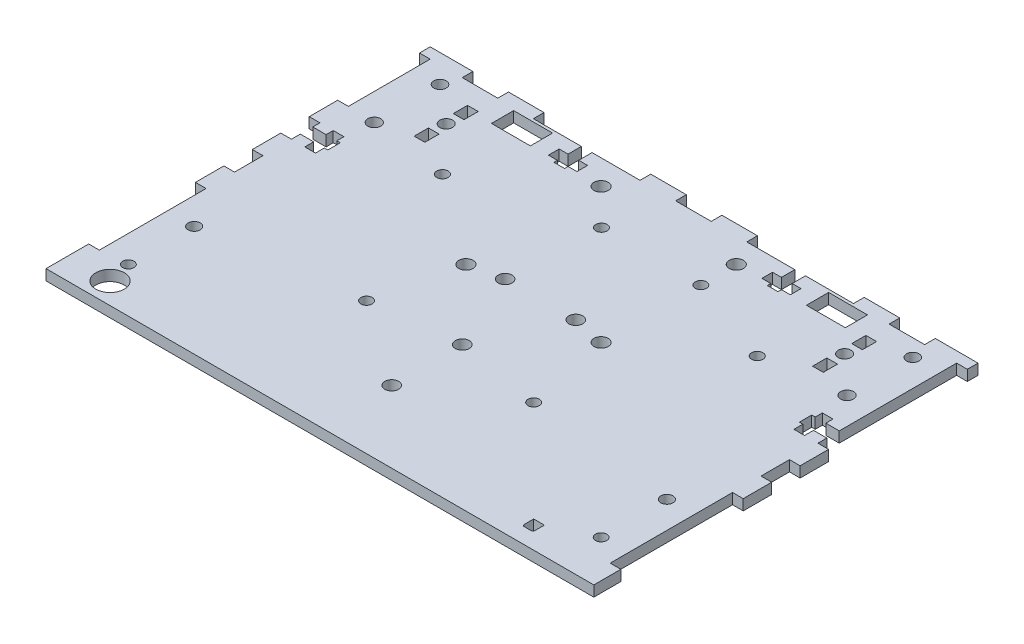
SolidWorks part; units mm, degrees
material "Balsa"
ref_plane "Alzado" through (0, 0, 0) normal (0, 0, 1) x (1, 0, 0)
ref_plane "Planta" through (0, 0, 0) normal (0, 1, 0) x (1, 0, 0)
ref_plane "Vista lateral" through (0, 0, 0) normal (1, 0, 0) x (0, 0, -1)
sketch "Croquis1" plane through (0, 0, 0) normal (0, 1, 0) x (1, 0, 0)
  line L0 (-77, 0) -> (-74, 0) construction
  line L1 (-77, -54) -> (77, -54)
  line L2 (-77, -54) -> (-77, 54)
  line L3 (-77, 54) -> (77, 54)
  line L4 (77, -54) -> (77, 54)
  line L5 (-77, -54) -> (77, 54) construction
  line L6 (-77, 54) -> (77, -54) construction
  line L7 (0, -54) -> (0, 54) construction
  line L8 (-74, 54) -> (-74, -54) construction
  line L9 (-77, -42) -> (-74, -42)
  line L10 (-77, 4) -> (-74, 4)
  line L11 (-77, 4) -> (-77, -4)
  line L12 (-77, -4) -> (-74, -4)
  line L13 (-74, 4) -> (-74, -4)
  line L14 (-77, 12) -> (-74, 12)
  line L15 (-77, 12) -> (-77, 20)
  line L16 (-77, 20) -> (-74, 20)
  line L17 (-74, 12) -> (-74, 20)
  line L22 (-77, 28) -> (-74, 28)
  line L23 (-77, 28) -> (-77, 42)
  line L24 (-77, 42) -> (-74, 42)
  line L25 (-74, 28) -> (-74, 42)
  line L26 (-74, -28) -> (-74, -42)
  line L27 (-77, -28) -> (-74, -28)
  line L28 (-77, -28) -> (-77, -42)
  line L29 (-77, -20) -> (-74, -20)
  line L30 (-74, -12) -> (-74, -20)
  line L31 (-77, -12) -> (-74, -12)
  line L32 (-77, -12) -> (-77, -20)
  line L33 (77, 42) -> (74, 42)
  line L34 (74, 28) -> (74, 42)
  line L35 (77, 28) -> (74, 28)
  line L36 (77, 28) -> (77, 42)
  line L37 (77, -28) -> (77, -42)
  line L38 (77, -28) -> (74, -28)
  line L39 (74, -28) -> (74, -42)
  line L40 (77, -42) -> (74, -42)
  line L41 (77, -12) -> (77, -20)
  line L42 (77, -12) -> (74, -12)
  line L43 (74, -12) -> (74, -20)
  line L44 (77, -20) -> (74, -20)
  line L45 (77, 20) -> (74, 20)
  line L46 (74, 12) -> (74, 20)
  line L47 (77, 12) -> (74, 12)
  line L48 (77, 12) -> (77, 20)
  line L49 (77, -4) -> (74, -4)
  line L50 (74, 4) -> (74, -4)
  line L51 (77, 4) -> (74, 4)
  line L52 (77, 4) -> (77, -4)
  line L53 (-77, 51) -> (77, 51) construction
  line L54 (-55, 51) -> (-65, 51)
  line L55 (-5, 54) -> (5, 54)
  line L56 (-5, 54) -> (-5, 51)
  line L57 (-5, 51) -> (5, 51)
  line L58 (5, 54) -> (5, 51)
  line L59 (15, 54) -> (45, 54)
  line L60 (15, 54) -> (15, 51)
  line L61 (15, 51) -> (45, 51)
  line L62 (45, 54) -> (45, 51)
  line L63 (55, 54) -> (65, 54)
  line L64 (55, 54) -> (55, 51)
  line L65 (55, 51) -> (65, 51)
  line L66 (65, 54) -> (65, 51)
  line L67 (-65, 54) -> (-65, 51)
  line L68 (-55, 54) -> (-65, 54)
  line L69 (-55, 54) -> (-55, 51)
  line L70 (-15, 51) -> (-45, 51)
  line L71 (-45, 54) -> (-45, 51)
  line L72 (-15, 54) -> (-45, 54)
  line L73 (-15, 54) -> (-15, 51)
  line L74 (-77, -48) -> (77, -48) construction
  line L75 (-30, 51) -> (-30, 10.4132) construction
  line L76 (53, -49.6) -> (55, -49.6)
  line L77 (52.5, -49.1) -> (52.5, -46.4)
  line L78 (52.5, -46.4) -> (55.5, -46.4)
  line L79 (55.5, -49.1) -> (55.5, -46.4)
  line L80 (52.5, -49.6) -> (55.5, -46.4) construction
  line L81 (52.5, -46.4) -> (55.5, -49.6) construction
  line L83 (-74, 1.5) -> (-74, -1.5)
  line L90 (-31.5, 51) -> (-28.5, 51)
  line L91 (-31.5, 51) -> (-31.5, 43.27)
  line L92 (-31.5, 43.27) -> (-28.5, 43.27)
  line L93 (-28.5, 51) -> (-28.5, 43.27)
  line L94 (-34, 47.25) -> (-26, 47.25)
  line L95 (-34, 47.25) -> (-34, 44.25)
  line L96 (-34, 44.25) -> (-26, 44.25)
  line L97 (-26, 47.25) -> (-26, 44.25)
  line L98 (31.5, 43.27) -> (28.5, 43.27)
  line L99 (28.5, 51) -> (28.5, 43.27)
  line L100 (31.5, 51) -> (28.5, 51)
  line L101 (31.5, 51) -> (31.5, 43.27)
  line L102 (34, 44.25) -> (26, 44.25)
  line L103 (26, 47.25) -> (26, 44.25)
  line L104 (34, 47.25) -> (26, 47.25)
  line L105 (34, 47.25) -> (34, 44.25)
  line L109 (74, 1.5) -> (74, -1.5)
  line L114 (-74, 16) -> (74, 16) construction
  line L115 (74, 17.9921) -> (66.27, 17.9921)
  line L116 (-74, 14.4979) -> (-66.27, 14.4979)
  line L117 (-74, 14.4979) -> (-74, 17.9921)
  line L118 (-74, 17.9921) -> (-66.27, 17.9921)
  line L119 (-66.27, 14.4979) -> (-66.27, 17.9921)
  line L120 (-70.25, 12) -> (-67.25, 12)
  line L121 (-70.25, 12) -> (-70.25, 20)
  line L122 (-70.25, 20) -> (-67.25, 20)
  line L123 (-67.25, 12) -> (-67.25, 20)
  line L124 (66.27, 14.4979) -> (66.27, 17.9921)
  line L125 (74, 0) -> (77, 0) construction
  line L126 (74, 14.4979) -> (66.27, 14.4979)
  line L127 (74, 14.4979) -> (74, 17.9921)
  line L128 (70.25, 20) -> (67.25, 20)
  line L129 (67.25, 12) -> (67.25, 20)
  line L130 (70.25, 12) -> (67.25, 12)
  line L131 (70.25, 12) -> (70.25, 20)
  circle A0 centre (-65, -48) radius 4
  arc A1 (55.5, -49.1) -> (55, -49.6) centre (55, -49.1) cw
  arc A2 (53, -49.6) -> (52.5, -49.1) centre (53, -49.1) cw
  point P0 (0, 0)
  point P78 (54, -48)
  point P123 (-75.5, 4)
  dimension "D17" = 8
  dimension "D22" = 0.5
  dimension "D1" = 108
  dimension "D2" = 154
  dimension "D3" = 3
  dimension "D4" = 4
  dimension "D5" = 3
  dimension "D6" = 8
  dimension "D7" = 8
  dimension "D8" = 8
  dimension "D9" = 14
  dimension "D10" = 3
  dimension "D11" = 5
  dimension "D12" = 10
  dimension "D13" = 10
  dimension "D14" = 30
  dimension "D15" = 10
  dimension "D16" = 10
  dimension "D18" = 6
  dimension "D19" = 23
  dimension "D20" = 3.2
  dimension "D21" = 3
  dimension "D23" = 12
  dimension "D31" = 3
  dimension "D32" = 8
  dimension "D33" = 1.5
  dimension "D34" = 4
  dimension "D35" = 0.98
  dimension "D36" = 7.73
  dimension "D37" = 8
  dimension "D38" = 7.73
  dimension "D39" = 3.4942
  dimension "D40" = 1.5021
  dimension "D41" = 0.98
  dimension "D42" = 8
  dimension "D43" = 4
  dimension "D44" = 3
extrude "Saliente-Extruir1" add sketch "Croquis1" along normal mid plane 2.9945
sketch "Croquis12" plane through (0, -1.4973, 0) normal (0, -1, 0) x (1, 0, 0)
  line L0 (77, 54) -> (77, 42) construction
  line L1 (-74, -51) -> (-77, -51)
  line L2 (-74, -51) -> (-74, -28)
  line L3 (-74, -28) -> (-77, -28)
  line L4 (-77, -51) -> (-77, -28)
  line L5 (-74, 20) -> (-77, 20)
  line L6 (-74, 20) -> (-74, 28)
  line L7 (-74, 28) -> (-77, 28)
  line L8 (-77, 20) -> (-77, 28)
  line L9 (74, -20) -> (77, -20)
  line L10 (74, -20) -> (74, -28)
  line L11 (74, -28) -> (77, -28)
  line L12 (77, -20) -> (77, -28)
  line L13 (74, 28) -> (77, 28)
  line L14 (74, 28) -> (74, 46.4)
  line L15 (74, 46.4) -> (77, 46.4)
  line L16 (77, 28) -> (77, 46.4)
  line L17 (77, -42) -> (77, -54) construction
  line L18 (74, -42) -> (77, -42)
  line L19 (74, -42) -> (74, -51)
  line L20 (74, -51) -> (77, -51)
  line L21 (77, -42) -> (77, -51)
extrude "Cortar-Extruir10" cut sketch "Croquis12" against normal blind 10
sketch "Croquis13" plane through (0, -1.4973, 0) normal (0, -1, 0) x (1, 0, 0)
  line L1 (77, 20) -> (74, 20)
  line L2 (77, 20) -> (77, 28)
  line L3 (77, 28) -> (74, 28)
  line L4 (74, 20) -> (74, 28)
extrude "Cortar-Extruir11" cut sketch "Croquis13" against normal blind 10
sketch "Croquis15" plane through (0, 1.4973, 0) normal (0, 1, 0) x (1, 0, 0)
  circle A0 centre (-8.89, 34.0361) radius 1.5875
  circle A1 centre (19.05, 34.0361) radius 1.5875
  circle A2 centre (24.13, -18.0339) radius 1.5875
  circle A3 centre (-24.13, -16.7639) radius 1.5875
extrude "Cortar-Extruir13" cut sketch "Croquis15" against normal blind 10
sketch "Croquis17" plane through (0, 1.4973, 0) normal (0, 1, 0) x (1, 0, 0)
  line L0 (72.1688, -24.6615) -> (72.1688, 30.6593) construction
  line L1 (72.1688, 2.9989) -> (49.0679, 2.9989) construction
  circle A0 centre (66.448, -41.3962) radius 1.5723
  circle A1 centre (66.448, -22.8957) radius 1.7053
sketch "Croquis16" plane through (0, 1.4973, 0) normal (0, 1, 0) x (1, 0, 0)
  circle A0 centre (-6.8282, -1.45) radius 2.1
  circle A1 centre (-44.8282, -1.45) radius 2.1
  circle A2 centre (-6.8282, -39.45) radius 2.1
  circle A3 centre (-44.8282, -39.45) radius 2
  circle A4 centre (30.775, -4.4) radius 1.9519
  circle A5 centre (10.925, -4.4) radius 1.95
  dimension "D1" = 3.9
extrude "Cortar-Extruir14" [suppressed] cut sketch "Croquis16" against normal blind 10
sketch "Croquis18" plane through (0, 1.4973, 0) normal (0, 1, 0) x (1, 0, 0)
  line L0 (0, 0) -> (0, 34.2841) construction
  circle A0 centre (66.448, -22.8957) radius 1.7053
  circle A1 centre (66.448, -41.3962) radius 1.5723
  circle A2 centre (66.448, 46.2165) radius 1.7517
  circle A3 centre (66.448, 27.7417) radius 1.8229
  circle A4 centre (-66.448, 27.7417) radius 1.8229
  circle A5 centre (-66.448, 46.2165) radius 1.7517
  circle A6 centre (-66.448, -41.3962) radius 1.5723
  circle A7 centre (-66.448, -22.8957) radius 1.7053
extrude "Cortar-Extruir15" cut sketch "Croquis18" against normal blind 10
sketch "Croquis19" plane through (0, 1.4973, 0) normal (0, 1, 0) x (1, 0, 0)
  line L0 (-56, 34) -> (-56, 41) construction
  line L1 (-57.5, 30) -> (-54.5, 30)
  line L2 (-57.5, 30) -> (-57.5, 34)
  line L3 (-57.5, 34) -> (-54.5, 34)
  line L4 (-54.5, 30) -> (-54.5, 34)
  line L5 (-56, 37.5) -> (-50.4082, 37.5) construction
  line L6 (-57.5, 41) -> (-54.5, 41)
  line L7 (-57.5, 45) -> (-57.5, 41)
  line L8 (-57.5, 45) -> (-54.5, 45)
  line L9 (-54.5, 45) -> (-54.5, 41)
  line L10 (0, 0) -> (0, 27.6562) construction
  line L11 (56, 37.5) -> (50.4082, 37.5) construction
  line L12 (56, 34) -> (56, 41) construction
  line L13 (54.5, 45) -> (54.5, 41)
  line L14 (57.5, 45) -> (54.5, 45)
  line L15 (57.5, 45) -> (57.5, 41)
  line L16 (57.5, 41) -> (54.5, 41)
  line L17 (54.5, 30) -> (54.5, 34)
  line L18 (57.5, 34) -> (54.5, 34)
  line L19 (57.5, 30) -> (57.5, 34)
  line L20 (57.5, 30) -> (54.5, 30)
  circle A0 centre (-56, 37.5) radius 1.8
  circle A1 centre (56, 37.5) radius 1.8
  dimension "D1" = 3.6
extrude "Cortar-Extruir16" cut sketch "Croquis19" against normal blind 10
sketch "Croquis20" plane through (0, 1.4973, 0) normal (0, 1, 0) x (1, 0, 0)
  line L1 (-38.7976, 43.9593) -> (-49.7367, 43.9593)
  line L2 (-38.7976, 43.9593) -> (-38.7976, 50.2033)
  line L3 (-38.7976, 50.2033) -> (-49.7367, 50.2033)
  line L4 (-49.7367, 43.9593) -> (-49.7367, 50.2033)
  circle A0 centre (-44.25, 24.7) radius 1.6
extrude "Cortar-Extruir17" cut sketch "Croquis20" against normal blind 10
mirror "Simetría1" about plane through (0, 0, 0) normal (1, 0, 0) of "Cortar-Extruir17"
sketch "Croquis21" plane through (0, 1.4973, 0) normal (0, 1, 0) x (1, 0, 0)
  circle A0 centre (0, -33.825) radius 1.9519
  circle A1 centre (0, -13.975) radius 1.9519
  circle A2 centre (19, 6.05) radius 2
  circle A3 centre (19, 44.05) radius 2
  circle A4 centre (-19, 44.05) radius 2
  circle A5 centre (-19, 6.05) radius 2
extrude "Cortar-Extruir18" cut sketch "Croquis21" against normal blind 10
sketch "Croquis22" plane through (0, 1.4973, 0) normal (0, 1, 0) x (1, 0, 0)
  circle A0 centre (-9.925, 8) radius 1.9519
  circle A1 centre (9.925, 8) radius 1.9519
extrude "Cortar-Extruir19" cut sketch "Croquis22" against normal blind 10
sketch "Croquis23" plane through (0, 1.4973, 0) normal (0, 1, 0) x (1, 0, 0)
  line L0 (-68.3649, 27.6945) -> (-64.3832, 27.6945)
  line L1 (-68.4388, 46.0665) -> (-64.4571, 46.0665)
  line L2 (-68.4388, 46.0665) -> (-68.4388, 46.3665)
  line L3 (-68.4388, 46.3665) -> (-64.4571, 46.3665)
  line L4 (-64.4571, 46.0665) -> (-64.4571, 46.3665)
  line L5 (-68.4388, 46.0665) -> (-64.4571, 46.3665) construction
  line L6 (-68.4388, 46.3665) -> (-64.4571, 46.0665) construction
  line L7 (-66.598, 44.2173) -> (-66.298, 44.2173)
  line L8 (-66.598, 44.2173) -> (-66.598, 48.2158)
  line L9 (-66.598, 48.2158) -> (-66.298, 48.2158)
  line L10 (-66.298, 44.2173) -> (-66.298, 48.2158)
  line L11 (-66.598, 44.2173) -> (-66.298, 48.2158) construction
  line L12 (-66.598, 48.2158) -> (-66.298, 44.2173) construction
  line L13 (-68.3649, 27.6945) -> (-68.3649, 27.9945)
  line L14 (-68.3649, 27.9945) -> (-64.3832, 27.9945)
  line L15 (-64.3832, 27.6945) -> (-64.3832, 27.9945)
  line L16 (-68.3649, 27.6945) -> (-64.3832, 27.9945) construction
  line L17 (-68.3649, 27.9945) -> (-64.3832, 27.6945) construction
  line L18 (-66.524, 25.8453) -> (-66.224, 25.8453)
  line L19 (-66.524, 25.8453) -> (-66.524, 29.8438)
  line L20 (-66.524, 29.8438) -> (-66.224, 29.8438)
  line L21 (-66.224, 25.8453) -> (-66.224, 29.8438)
  line L22 (-66.524, 25.8453) -> (-66.224, 29.8438) construction
  line L23 (-66.524, 29.8438) -> (-66.224, 25.8453) construction
  line L28 (-68.4428, -41.592) -> (-64.4611, -41.592)
  line L29 (-68.4428, -41.592) -> (-68.4428, -41.292)
  line L34 (-68.4428, -41.292) -> (-64.4611, -41.292)
  line L35 (-64.4611, -41.592) -> (-64.4611, -41.292)
  line L40 (-68.4428, -41.592) -> (-64.4611, -41.292) construction
  line L41 (-68.4428, -41.292) -> (-64.4611, -41.592) construction
  line L46 (-66.6019, -43.4413) -> (-66.3019, -43.4413)
  line L47 (-66.6019, -43.4413) -> (-66.6019, -39.4428)
  line L48 (-66.6019, -39.4428) -> (-66.3019, -39.4428)
  line L49 (-66.3019, -43.4413) -> (-66.3019, -39.4428)
  line L50 (-66.6019, -43.4413) -> (-66.3019, -39.4428) construction
  line L51 (-66.6019, -39.4428) -> (-66.3019, -43.4413) construction
  line L52 (-68.5357, -22.9687) -> (-64.5539, -22.9687)
  line L53 (-68.5357, -22.9687) -> (-68.5357, -22.6687)
  line L54 (-68.5357, -22.6687) -> (-64.5539, -22.6687)
  line L55 (-64.5539, -22.9687) -> (-64.5539, -22.6687)
  line L56 (-68.5357, -22.9687) -> (-64.5539, -22.6687) construction
  line L57 (-68.5357, -22.6687) -> (-64.5539, -22.9687) construction
  line L58 (-66.6948, -24.8179) -> (-66.3948, -24.8179)
  line L59 (-66.6948, -24.8179) -> (-66.6948, -20.8194)
  line L60 (-66.6948, -20.8194) -> (-66.3948, -20.8194)
  line L61 (-66.3948, -24.8179) -> (-66.3948, -20.8194)
  line L62 (-66.6948, -24.8179) -> (-66.3948, -20.8194) construction
  line L63 (-66.6948, -20.8194) -> (-66.3948, -24.8179) construction
  line L64 (64.4797, -41.6408) -> (68.4615, -41.6408)
  line L65 (64.4797, -41.6408) -> (64.4797, -41.3408)
  line L66 (64.4797, -41.3408) -> (68.4615, -41.3408)
  line L67 (68.4615, -41.6408) -> (68.4615, -41.3408)
  line L68 (64.4797, -41.6408) -> (68.4615, -41.3408) construction
  line L69 (64.4797, -41.3408) -> (68.4615, -41.6408) construction
  line L70 (66.3206, -43.4901) -> (66.6206, -43.4901)
  line L71 (66.3206, -43.4901) -> (66.3206, -39.4915)
  line L72 (66.3206, -39.4915) -> (66.6206, -39.4915)
  line L73 (66.6206, -43.4901) -> (66.6206, -39.4915)
  line L74 (66.3206, -43.4901) -> (66.6206, -39.4915) construction
  line L75 (66.3206, -39.4915) -> (66.6206, -43.4901) construction
  line L76 (64.4625, -22.7879) -> (68.4443, -22.7879)
  line L77 (64.4625, -22.7879) -> (64.4625, -22.4879)
  line L78 (64.4625, -22.4879) -> (68.4443, -22.4879)
  line L79 (68.4443, -22.7879) -> (68.4443, -22.4879)
  line L80 (64.4625, -22.7879) -> (68.4443, -22.4879) construction
  line L81 (64.4625, -22.4879) -> (68.4443, -22.7879) construction
  line L82 (66.3034, -24.6372) -> (66.6034, -24.6372)
  line L83 (66.3034, -24.6372) -> (66.3034, -20.6387)
  line L84 (66.3034, -20.6387) -> (66.6034, -20.6387)
  line L85 (66.6034, -24.6372) -> (66.6034, -20.6387)
  line L86 (66.3034, -24.6372) -> (66.6034, -20.6387) construction
  line L87 (66.3034, -20.6387) -> (66.6034, -24.6372) construction
  line L88 (64.4162, 27.4546) -> (68.3979, 27.4546)
  line L89 (64.4162, 27.4546) -> (64.4162, 27.7546)
  line L90 (64.4162, 27.7546) -> (68.3979, 27.7546)
  line L91 (68.3979, 27.4546) -> (68.3979, 27.7546)
  line L92 (64.4162, 27.4546) -> (68.3979, 27.7546) construction
  line L93 (64.4162, 27.7546) -> (68.3979, 27.4546) construction
  line L94 (66.2571, 25.6054) -> (66.5571, 25.6054)
  line L95 (66.2571, 25.6054) -> (66.2571, 29.6039)
  line L96 (66.2571, 29.6039) -> (66.5571, 29.6039)
  line L97 (66.5571, 25.6054) -> (66.5571, 29.6039)
  line L98 (66.2571, 25.6054) -> (66.5571, 29.6039) construction
  line L99 (66.2571, 29.6039) -> (66.5571, 25.6054) construction
  line L100 (64.3241, 46.1595) -> (68.3059, 46.1595)
  line L101 (64.3241, 46.1595) -> (64.3241, 46.4595)
  line L102 (64.3241, 46.4595) -> (68.3059, 46.4595)
  line L103 (68.3059, 46.1595) -> (68.3059, 46.4595)
  line L104 (64.3241, 46.1595) -> (68.3059, 46.4595) construction
  line L105 (64.3241, 46.4595) -> (68.3059, 46.1595) construction
  line L106 (66.165, 44.3102) -> (66.465, 44.3102)
  line L107 (66.165, 44.3102) -> (66.165, 48.3088)
  line L108 (66.165, 48.3088) -> (66.465, 48.3088)
  line L109 (66.465, 44.3102) -> (66.465, 48.3088)
  line L110 (66.165, 44.3102) -> (66.465, 48.3088) construction
  line L111 (66.165, 48.3088) -> (66.465, 44.3102) construction
  line L112 (-1.9679, -33.9155) -> (2.0138, -33.9155)
  line L113 (-1.9679, -33.9155) -> (-1.9679, -33.6155)
  line L114 (-1.9679, -33.6155) -> (2.0138, -33.6155)
  line L115 (2.0138, -33.9155) -> (2.0138, -33.6155)
  line L116 (-1.9679, -33.9155) -> (2.0138, -33.6155) construction
  line L117 (-1.9679, -33.6155) -> (2.0138, -33.9155) construction
  line L118 (-0.127, -35.7648) -> (0.173, -35.7648)
  line L119 (-0.127, -35.7648) -> (-0.127, -31.7663)
  line L120 (-0.127, -31.7663) -> (0.173, -31.7663)
  line L121 (0.173, -35.7648) -> (0.173, -31.7663)
  line L122 (-0.127, -35.7648) -> (0.173, -31.7663) construction
  line L123 (-0.127, -31.7663) -> (0.173, -35.7648) construction
  line L128 (-21.6618, 43.8673) -> (-16.5489, 43.8673)
  line L129 (-21.6618, 43.8673) -> (-21.6618, 44.1673)
  line L134 (-21.6618, 44.1673) -> (-16.5489, 44.1673)
  line L135 (-16.5489, 43.8673) -> (-16.5489, 44.1673)
  line L136 (-26.0528, -16.9261) -> (-22.0711, -16.9261)
  line L137 (-26.0528, -16.9261) -> (-26.0528, -16.6261)
  line L138 (-26.0528, -16.6261) -> (-22.0711, -16.6261)
  line L139 (-22.0711, -16.9261) -> (-22.0711, -16.6261)
  line L140 (-26.0528, -16.9261) -> (-22.0711, -16.6261) construction
  line L141 (-26.0528, -16.6261) -> (-22.0711, -16.9261) construction
  line L142 (-24.212, -18.7754) -> (-23.912, -18.7754)
  line L143 (-24.212, -18.7754) -> (-24.212, -14.7769)
  line L144 (-24.212, -14.7769) -> (-23.912, -14.7769)
  line L145 (-23.912, -18.7754) -> (-23.912, -14.7769)
  line L146 (-24.212, -18.7754) -> (-23.912, -14.7769) construction
  line L147 (-24.212, -14.7769) -> (-23.912, -18.7754) construction
  line L148 (22.1176, -18.1484) -> (26.0994, -18.1484)
  line L149 (22.1176, -18.1484) -> (22.1176, -17.8484)
  line L150 (22.1176, -17.8484) -> (26.0994, -17.8484)
  line L151 (26.0994, -18.1484) -> (26.0994, -17.8484)
  line L152 (22.1176, -18.1484) -> (26.0994, -17.8484) construction
  line L153 (22.1176, -17.8484) -> (26.0994, -18.1484) construction
  line L154 (23.9585, -19.9977) -> (24.2585, -19.9977)
  line L155 (23.9585, -19.9977) -> (23.9585, -15.9992)
  line L156 (23.9585, -15.9992) -> (24.2585, -15.9992)
  line L157 (24.2585, -19.9977) -> (24.2585, -15.9992)
  line L158 (23.9585, -19.9977) -> (24.2585, -15.9992) construction
  line L159 (23.9585, -15.9992) -> (24.2585, -19.9977) construction
  line L164 (-21.6618, 43.8673) -> (-16.5489, 44.1673) construction
  line L165 (-21.6618, 44.1673) -> (-16.5489, 43.8673) construction
  line L170 (-19.2554, 41.2583) -> (-18.9554, 41.2583)
  line L171 (-19.2554, 41.2583) -> (-19.2554, 46.7764)
  line L172 (16.9745, 33.9938) -> (20.9562, 33.9938)
  line L173 (16.9745, 33.9938) -> (16.9745, 34.2938)
  line L174 (16.9745, 34.2938) -> (20.9562, 34.2938)
  line L175 (20.9562, 33.9938) -> (20.9562, 34.2938)
  line L176 (16.9745, 33.9938) -> (20.9562, 34.2938) construction
  line L177 (16.9745, 34.2938) -> (20.9562, 33.9938) construction
  line L178 (18.8154, 32.1445) -> (19.1154, 32.1445)
  line L179 (18.8154, 32.1445) -> (18.8154, 36.143)
  line L180 (18.8154, 36.143) -> (19.1154, 36.143)
  line L181 (19.1154, 32.1445) -> (19.1154, 36.143)
  line L182 (18.8154, 32.1445) -> (19.1154, 36.143) construction
  line L183 (18.8154, 36.143) -> (19.1154, 32.1445) construction
  line L184 (-10.8981, 33.9741) -> (-6.9164, 33.9741)
  line L185 (-10.8981, 33.9741) -> (-10.8981, 34.2741)
  line L186 (-10.8981, 34.2741) -> (-6.9164, 34.2741)
  line L187 (-6.9164, 33.9741) -> (-6.9164, 34.2741)
  line L188 (-10.8981, 33.9741) -> (-6.9164, 34.2741) construction
  line L189 (-10.8981, 34.2741) -> (-6.9164, 33.9741) construction
  line L190 (-9.0572, 32.1249) -> (-8.7572, 32.1249)
  line L191 (-9.0572, 32.1249) -> (-9.0572, 36.1234)
  line L192 (-9.0572, 36.1234) -> (-8.7572, 36.1234)
  line L193 (-8.7572, 32.1249) -> (-8.7572, 36.1234)
  line L194 (-9.0572, 32.1249) -> (-8.7572, 36.1234) construction
  line L195 (-9.0572, 36.1234) -> (-8.7572, 32.1249) construction
  line L196 (-2.5518, -13.8532) -> (2.561, -13.8532)
  line L197 (-2.5518, -13.8532) -> (-2.5518, -13.5532)
  line L198 (-2.5518, -13.5532) -> (2.561, -13.5532)
  line L199 (2.561, -13.8532) -> (2.561, -13.5532)
  line L200 (-2.5518, -13.8532) -> (2.561, -13.5532) construction
  line L201 (-2.5518, -13.5532) -> (2.561, -13.8532) construction
  line L202 (-0.1454, -16.4622) -> (0.1546, -16.4622)
  line L203 (-0.1454, -16.4622) -> (-0.1454, -10.9442)
  line L204 (-0.1454, -10.9442) -> (0.1546, -10.9442)
  line L205 (0.1546, -16.4622) -> (0.1546, -10.9442)
  line L206 (-0.1454, -16.4622) -> (0.1546, -10.9442) construction
  line L207 (-0.1454, -10.9442) -> (0.1546, -16.4622) construction
  line L208 (-21.5314, 5.9128) -> (-16.4185, 5.9128)
  line L209 (-21.5314, 5.9128) -> (-21.5314, 6.2128)
  line L210 (-21.5314, 6.2128) -> (-16.4185, 6.2128)
  line L211 (-16.4185, 5.9128) -> (-16.4185, 6.2128)
  line L212 (-21.5314, 5.9128) -> (-16.4185, 6.2128) construction
  line L213 (-21.5314, 6.2128) -> (-16.4185, 5.9128) construction
  line L214 (-19.125, 3.3038) -> (-18.825, 3.3038)
  line L215 (-19.125, 3.3038) -> (-19.125, 8.8218)
  line L216 (-19.125, 8.8218) -> (-18.825, 8.8218)
  line L217 (-18.825, 3.3038) -> (-18.825, 8.8218)
  line L218 (-19.125, 3.3038) -> (-18.825, 8.8218) construction
  line L219 (-19.125, 8.8218) -> (-18.825, 3.3038) construction
  line L220 (-12.5705, 7.9158) -> (-7.4576, 7.9158)
  line L221 (-12.5705, 7.9158) -> (-12.5705, 8.2158)
  line L222 (-12.5705, 8.2158) -> (-7.4576, 8.2158)
  line L223 (-7.4576, 7.9158) -> (-7.4576, 8.2158)
  line L224 (-12.5705, 7.9158) -> (-7.4576, 8.2158) construction
  line L225 (-12.5705, 8.2158) -> (-7.4576, 7.9158) construction
  line L226 (-10.164, 5.3068) -> (-9.864, 5.3068)
  line L227 (-10.164, 5.3068) -> (-10.164, 10.8248)
  line L228 (-10.164, 10.8248) -> (-9.864, 10.8248)
  line L229 (-9.864, 5.3068) -> (-9.864, 10.8248)
  line L230 (-10.164, 5.3068) -> (-9.864, 10.8248) construction
  line L231 (-10.164, 10.8248) -> (-9.864, 5.3068) construction
  line L232 (7.3462, 7.9195) -> (12.4591, 7.9195)
  line L233 (7.3462, 7.9195) -> (7.3462, 8.2195)
  line L234 (7.3462, 8.2195) -> (12.4591, 8.2195)
  line L235 (12.4591, 7.9195) -> (12.4591, 8.2195)
  line L236 (7.3462, 7.9195) -> (12.4591, 8.2195) construction
  line L237 (7.3462, 8.2195) -> (12.4591, 7.9195) construction
  line L238 (9.7526, 5.3105) -> (10.0526, 5.3105)
  line L239 (9.7526, 5.3105) -> (9.7526, 10.8285)
  line L240 (9.7526, 10.8285) -> (10.0526, 10.8285)
  line L241 (10.0526, 5.3105) -> (10.0526, 10.8285)
  line L242 (9.7526, 5.3105) -> (10.0526, 10.8285) construction
  line L243 (9.7526, 10.8285) -> (10.0526, 5.3105) construction
  line L244 (16.2422, 5.9521) -> (21.3551, 5.9521)
  line L245 (16.2422, 5.9521) -> (16.2422, 6.2521)
  line L246 (16.2422, 6.2521) -> (21.3551, 6.2521)
  line L247 (21.3551, 5.9521) -> (21.3551, 6.2521)
  line L248 (16.2422, 5.9521) -> (21.3551, 6.2521) construction
  line L249 (16.2422, 6.2521) -> (21.3551, 5.9521) construction
  line L250 (18.6487, 3.3431) -> (18.9487, 3.3431)
  line L251 (18.6487, 3.3431) -> (18.6487, 8.8611)
  line L252 (18.6487, 8.8611) -> (18.9487, 8.8611)
  line L253 (18.9487, 3.3431) -> (18.9487, 8.8611)
  line L254 (18.6487, 3.3431) -> (18.9487, 8.8611) construction
  line L255 (18.6487, 8.8611) -> (18.9487, 3.3431) construction
  line L256 (-19.2554, 46.7764) -> (-18.9554, 46.7764)
  line L257 (-18.9554, 41.2583) -> (-18.9554, 46.7764)
  line L258 (-19.2554, 41.2583) -> (-18.9554, 46.7764) construction
  line L259 (-19.2554, 46.7764) -> (-18.9554, 41.2583) construction
  line L260 (16.2853, 43.9673) -> (21.3982, 43.9673)
  line L261 (16.2853, 43.9673) -> (16.2853, 44.2673)
  line L262 (16.2853, 44.2673) -> (21.3982, 44.2673)
  line L263 (21.3982, 43.9673) -> (21.3982, 44.2673)
  line L264 (16.2853, 43.9673) -> (21.3982, 44.2673) construction
  line L265 (16.2853, 44.2673) -> (21.3982, 43.9673) construction
  line L266 (18.6917, 41.3583) -> (18.9917, 41.3583)
  line L267 (18.6917, 41.3583) -> (18.6917, 46.8763)
  line L268 (18.6917, 46.8763) -> (18.9917, 46.8763)
  line L269 (18.9917, 41.3583) -> (18.9917, 46.8763)
  line L270 (18.6917, 41.3583) -> (18.9917, 46.8763) construction
  line L271 (18.6917, 46.8763) -> (18.9917, 41.3583) construction
  point P0 (-66.448, 46.2165)
  point P6 (-66.448, 46.2165)
  point P11 (-66.598, 48.2158)
  point P12 (-66.374, 27.8445)
  point P17 (-66.374, 27.8445)
  point P22 (-66.4519, -41.442)
  point P27 (-66.4519, -41.442)
  point P32 (-66.5448, -22.8187)
  point P37 (-66.5448, -22.8187)
  point P42 (66.4706, -41.4908)
  point P47 (66.4706, -41.4908)
  point P52 (66.4534, -22.6379)
  point P57 (66.4534, -22.6379)
  point P62 (66.4071, 27.6046)
  point P67 (66.4071, 27.6046)
  point P72 (66.315, 46.3095)
  point P77 (66.315, 46.3095)
  point P82 (0.023, -33.7655)
  point P87 (0.023, -33.7655)
  point P92 (-19.1054, 44.0173)
  point P97 (-19.1054, 44.0173)
  point P102 (-24.062, -16.7761)
  point P107 (-24.062, -16.7761)
  point P112 (24.1085, -17.9984)
  point P117 (24.1085, -17.9984)
  point P122 (18.8417, 44.1173)
  point P127 (18.8417, 44.1173)
  point P132 (18.9654, 34.1438)
  point P137 (18.9654, 34.1438)
  point P142 (-8.9072, 34.1241)
  point P147 (-8.9072, 34.1241)
  point P152 (0.0046, -13.7032)
  point P157 (0.0046, -13.7032)
  point P162 (0.1389, -16.0446)
  point P163 (0, 0)
  point P164 (0, 0)
  point P165 (-18.975, 6.0628)
  point P170 (-18.975, 6.0628)
  point P175 (-10.014, 8.0658)
  point P180 (-10.014, 8.0658)
  point P185 (9.9026, 8.0695)
  point P190 (9.9026, 8.0695)
  point P195 (18.7987, 6.1021)
  point P200 (18.7987, 6.1021)
  dimension "D1" = 0.3
  dimension "D2" = 0.3
  dimension "D3" = 0.3
  dimension "D4" = 0.3
  dimension "D5" = 0.3
  dimension "D6" = 0.3
  dimension "D7" = 0.3
  dimension "D8" = 0.3
  dimension "D9" = 0.3
  dimension "D10" = 0.3
  dimension "D11" = 0.3
  dimension "D12" = 0.3
  dimension "D13" = 0.3
  dimension "D14" = 0.3
  dimension "D15" = 0.3
  dimension "D16" = 0.3
  dimension "D17" = 0.3
  dimension "D18" = 0.3
  dimension "D19" = 0.3
  dimension "D20" = 0.3
  dimension "D21" = 0.3
  dimension "D22" = 0.3
  dimension "D23" = 0.3
  dimension "D24" = 0.3
  dimension "D25" = 0.3
  dimension "D26" = 0.3
  dimension "D27" = 0.3
  dimension "D28" = 0.3
  dimension "D29" = 0.3
  dimension "D30" = 0.3
  dimension "D31" = 0.3
  dimension "D32" = 0.3
  dimension "D33" = 0.3
  dimension "D34" = 0.3
  dimension "D35" = 0.3
  dimension "D36" = 0.3
  dimension "D37" = 0.3
  dimension "D38" = 0.3
  dimension "D39" = 0.3
  dimension "D40" = 0.3
